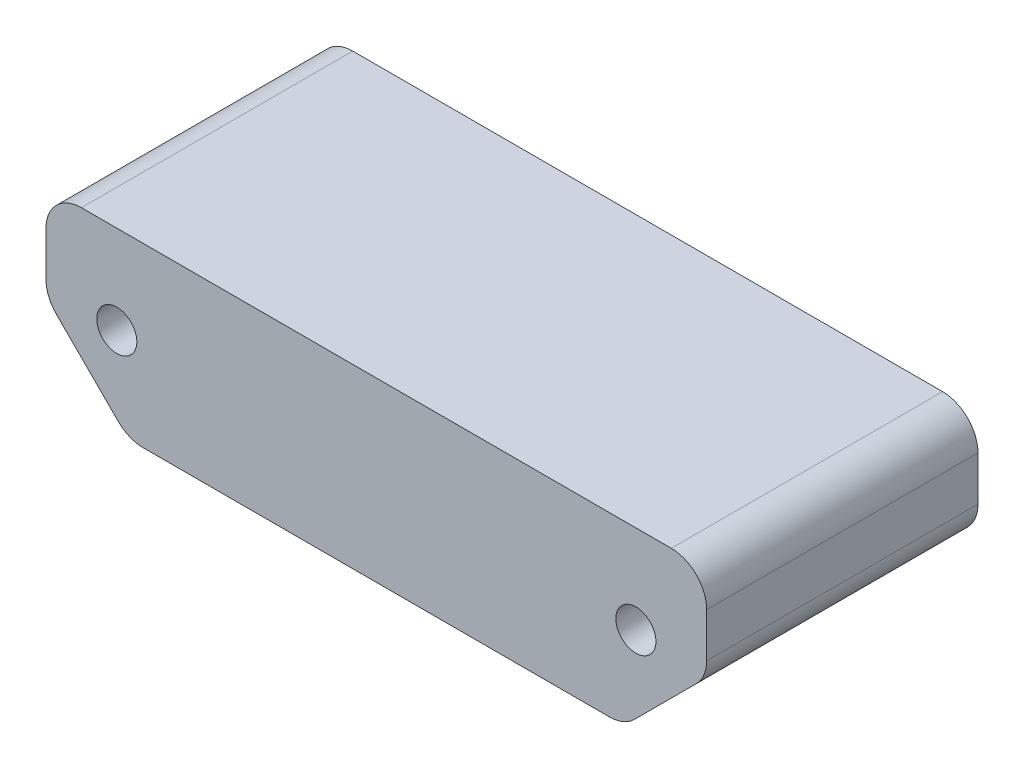
SolidWorks part; units mm, degrees
material "ABS"
ref_plane "前视基准面" through (0, 0, 0) normal (0, 0, 1) x (1, 0, 0)
ref_plane "上视基准面" through (0, 0, 0) normal (0, 1, 0) x (1, 0, 0)
ref_plane "右视基准面" through (0, 0, 0) normal (1, 0, 0) x (0, 0, -1)
other "Configuration Table"
sketch "草图1" plane through (0, 0, 0) normal (0, 0, 1) x (1, 0, 0)
  line L0 (-22, 0) -> (22, 0) construction
  line L1 (-28, -7.5) -> (28, -7.5)
  line L2 (-28, -7.5) -> (-28, 7.5)
  line L3 (-28, 7.5) -> (28, 7.5)
  line L4 (28, -7.5) -> (28, 7.5)
  line L5 (-28, -7.5) -> (28, 7.5) construction
  line L6 (-28, 7.5) -> (28, -7.5) construction
  line L7 (0, -7.5) -> (0, 7.5) construction
  circle A0 centre (22, 0) radius 1.7
  circle A1 centre (-22, 0) radius 1.7
  point P0 (0, 0)
  dimension "D4" = 3.4
  dimension "D1" = 56
  dimension "D2" = 15
  dimension "D3" = 44
extrude "凸台-拉伸1" add sketch "草图1" along normal blind 23
chamfer "倒角2" distance 7 angle 45 2 edges at (28, -7.5, 11.5) (-28, -7.5, 11.5)
fillet "圆角1" radius 3 6 edges at (21, -7.5, 11.5) (28, -0.5, 11.5) (28, 7.5, 11.5) (-28, 7.5, 11.5) (-21, -7.5, 11.5) (-28, -0.5, 11.5)
